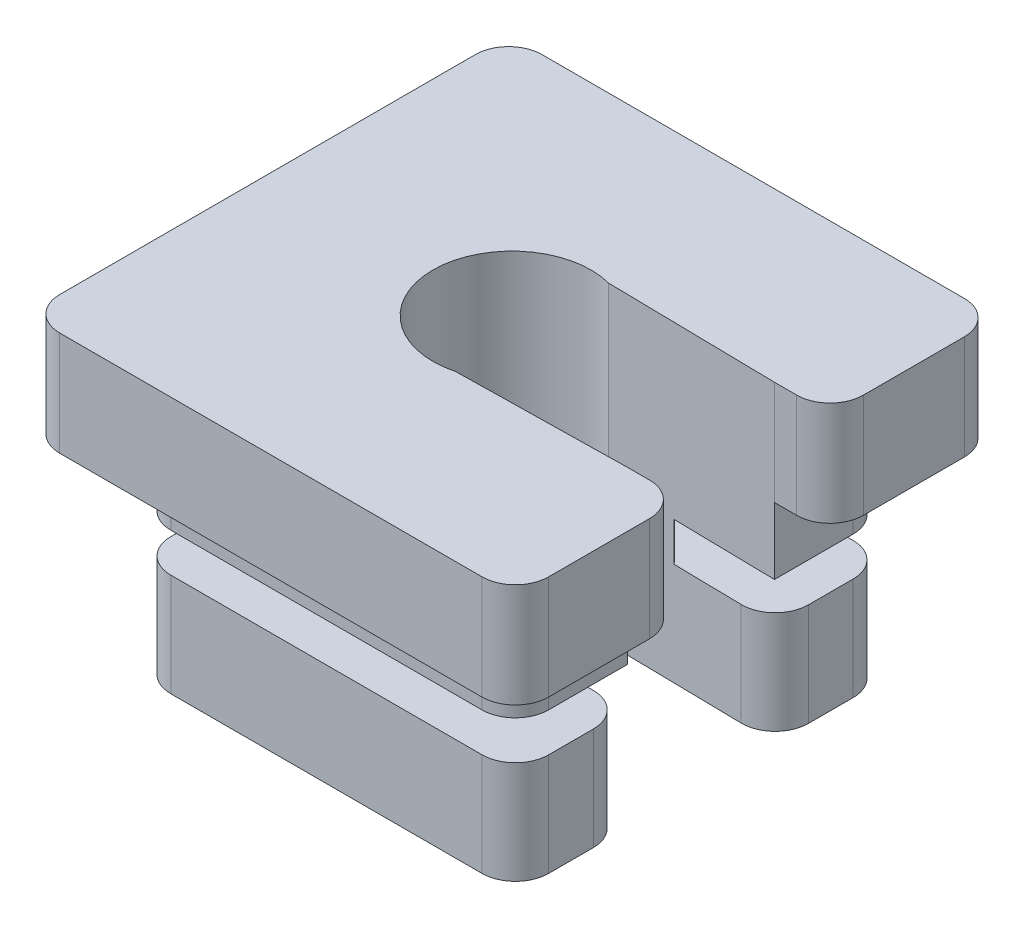
SolidWorks part; units mm, degrees
ref_plane "Front Plane" through (0, 0, 0) normal (0, 0, 1) x (1, 0, 0)
ref_plane "Top Plane" through (0, 0, 0) normal (0, 1, 0) x (1, 0, 0)
ref_plane "Right Plane" through (0, 0, 0) normal (1, 0, 0) x (0, 0, -1)
sketch "Sketch1" plane through (0, 0, 0) normal (0, 1, 0) x (1, 0, 0)
  line L0 (8.89, 5.9309) -> (14.3679, 5.9309)
  line L1 (8.89, -8.7376) -> (-8.89, -8.7376)
  line L2 (8.89, -8.7376) -> (8.89, 8.7376)
  line L3 (8.89, 8.7376) -> (-8.89, 8.7376)
  line L4 (-8.89, -8.7376) -> (-8.89, 8.7376)
  line L5 (8.89, -8.7376) -> (-8.89, 8.7376) construction
  line L6 (8.89, 8.7376) -> (-8.89, -8.7376) construction
  line L7 (0, 0) -> (14.3679, 0) construction
  line L8 (8.89, -5.9309) -> (14.3679, -5.9309)
  circle A0 centre (0, 0) radius 3.6195
  dimension "D1" = 7.239
  dimension "D2" = 17.4752
  dimension "D3" = 17.78
  dimension "D4" = 11.8618
sketch "Sketch2" plane through (0, 0, 0) normal (0, 1, 0) x (1, 0, 0)
  line L0 (8.89, -5.9309) -> (14.3679, -5.9309) construction
  line L1 (8.89, 5.9309) -> (14.3679, 5.9309) construction
  line L2 (8.89, -5.9309) -> (14.3679, -5.9309) construction
  line L3 (8.89, 5.9309) -> (14.3679, 5.9309) construction
  line L4 (-8.89, -8.7376) -> (8.89, -8.7376)
  line L5 (-8.89, 8.7376) -> (-8.89, -8.7376)
  line L6 (8.89, 8.7376) -> (-8.89, 8.7376)
  line L7 (8.89, -8.7376) -> (8.89, 8.7376)
  line L8 (-8.89, -8.7376) -> (8.89, -8.7376) construction
  line L9 (-8.89, 8.7376) -> (-8.89, -8.7376) construction
  line L10 (8.89, 8.7376) -> (-8.89, 8.7376) construction
  line L11 (8.89, -8.7376) -> (8.89, 8.7376) construction
  line L12 (8.64, 8.4876) -> (-8.64, 8.4876)
  line L13 (-8.64, 8.4876) -> (-8.64, -8.4876)
  line L14 (-8.64, -8.4876) -> (8.64, -8.4876)
  line L15 (8.64, -8.4876) -> (8.64, -3.3655)
  line L16 (0.9215, 3.5002) -> (8.64, 3.3655)
  line L17 (0, 0) -> (14.3679, 0) construction
  line L18 (0, 0) -> (14.3679, 0) construction
  line L19 (0.9215, -3.5002) -> (8.64, -3.3655)
  line L20 (8.64, 3.3655) -> (8.64, 8.4876)
  line L22 (8.64, -8.4876) -> (8.64, 8.4876) construction
  circle A1 centre (0, 0) radius 3.6195
  arc A2 (0.9215, 3.5002) -> (0.9215, -3.5002) centre (0, 0) ccw
  circle A3 centre (0, 0) radius 3.6195 construction
  dimension "D5" = 7.239
  dimension "D4" = 1
  dimension "D6" = 6.731
  dimension "D1" = 0
  dimension "D2" = 0
  dimension "D3" = 0.25
extrude "Boss-Extrude1" add sketch "Sketch2" along normal blind 9.525
sketch "Sketch3" plane through (0, 9.525, 0) normal (0, 1, 0) x (1, 0, 0)
  line L0 (11.18, 3.3655) -> (11.18, 11.0276)
  line L1 (11.18, 11.0276) -> (-11.18, 11.0276)
  line L2 (-11.18, 11.0276) -> (-11.18, -11.0276)
  line L3 (-11.18, -11.0276) -> (11.18, -11.0276)
  line L4 (11.18, -11.0276) -> (11.18, -3.3655)
  line L5 (8.64, 3.3655) -> (11.18, 3.3655)
  line L6 (8.64, -3.3655) -> (11.18, -3.3655)
  line L7 (8.64, 3.3655) -> (8.64, 8.4876)
  line L8 (8.64, 8.4876) -> (-8.64, 8.4876)
  line L9 (-8.64, 8.4876) -> (-8.64, -8.4876)
  line L10 (-8.64, -8.4876) -> (8.64, -8.4876)
  line L11 (8.64, -8.4876) -> (8.64, -3.3655)
  line L12 (8.64, -3.3655) -> (0.9215, -3.5002)
  line L13 (0.9215, 3.5002) -> (8.64, 3.3655)
  line L14 (8.64, 3.3655) -> (8.64, 8.4876) construction
  line L15 (8.64, 8.4876) -> (-8.64, 8.4876) construction
  line L16 (-8.64, 8.4876) -> (-8.64, -8.4876) construction
  line L17 (-8.64, -8.4876) -> (8.64, -8.4876) construction
  line L18 (8.64, -8.4876) -> (8.64, -3.3655) construction
  line L19 (8.64, -3.3655) -> (0.9215, -3.5002)
  line L20 (0.9215, 3.5002) -> (8.64, 3.3655)
  arc A1 (0.9215, 3.5002) -> (0.9215, -3.5002) centre (0, 0) ccw
  arc A2 (0.9215, 3.5002) -> (0.9215, -3.5002) centre (0, 0) ccw
  dimension "D1" = 0
  dimension "D2" = 2.54
extrude "Boss-Extrude2" add sketch "Sketch3" along normal blind 4.7625
ref_plane "Plane1" through (0, 6.477, 0) normal (0, -1, 0) x (-1, 0, 0)
sketch "Sketch4" plane through (0, 6.477, 0) normal (0, -1, 0) x (-1, 0, 0)
  line L0 (3.9702, 3.447) -> (8.64, 3.447)
  line L2 (0, 0) -> (8.64, 0) construction
  line L3 (3.9702, -3.447) -> (8.64, -3.447)
  line L4 (8.64, 3.447) -> (8.64, 8.4876)
  line L7 (-8.64, 8.4876) -> (-8.64, 3.3655)
  line L8 (-8.64, 3.3655) -> (-0.9215, 3.5002)
  line L9 (-0.9215, -3.5002) -> (-8.64, -3.3655)
  line L10 (-8.64, -3.3655) -> (-8.64, -8.4876)
  line L11 (-8.64, -8.4876) -> (8.64, -8.4876)
  line L12 (8.64, -8.4876) -> (8.64, 8.4876)
  line L13 (8.64, 8.4876) -> (-8.64, 8.4876)
  line L14 (-8.64, 8.4876) -> (-8.64, 3.3655)
  line L15 (-8.64, 3.3655) -> (-3.9702, 3.447)
  line L16 (-3.9702, -3.447) -> (-8.64, -3.3655)
  line L17 (-8.64, -3.3655) -> (-8.64, -8.4876)
  line L18 (-8.64, -8.4876) -> (8.64, -8.4876)
  line L19 (8.64, -8.4876) -> (8.64, -3.447)
  line L20 (8.64, 8.4876) -> (-8.64, 8.4876)
  arc A0 (-3.9702, -3.447) -> (3.9702, -3.447) centre (0, 0) ccw
  arc A1 (3.9702, 3.447) -> (-3.9702, 3.447) centre (0, 0) ccw
  arc A2 (-0.9215, -3.5002) -> (-0.9215, 3.5002) centre (0, 0) ccw
  point P16 (8.64, 0)
  dimension "D2" = 10.5156
  dimension "D1" = 0
extrude "Cut-Extrude1" cut sketch "Sketch4" along normal blind 1.778
fillet "Fillet1" radius 1.524 16 edges at (-11.18, 11.9062, 11.0276) (-8.64, 8.001, 8.4876) (8.64, 8.001, -8.4876) (8.64, 8.001, 8.4876) (11.18, 11.9062, 11.0276) (11.18, 11.9062, -11.0276) (-11.18, 11.9062, -11.0276) (-8.64, 8.001, -8.4876) (-8.64, 2.3495, -8.4876) (8.64, 2.3495, -8.4876) (-8.64, 2.3495, 8.4876) (8.64, 2.3495, 8.4876) (8.64, 2.3495, -3.3655) (8.64, 2.3495, 3.3655) (11.18, 11.9062, -3.3655) (11.18, 11.9062, 3.3655)
